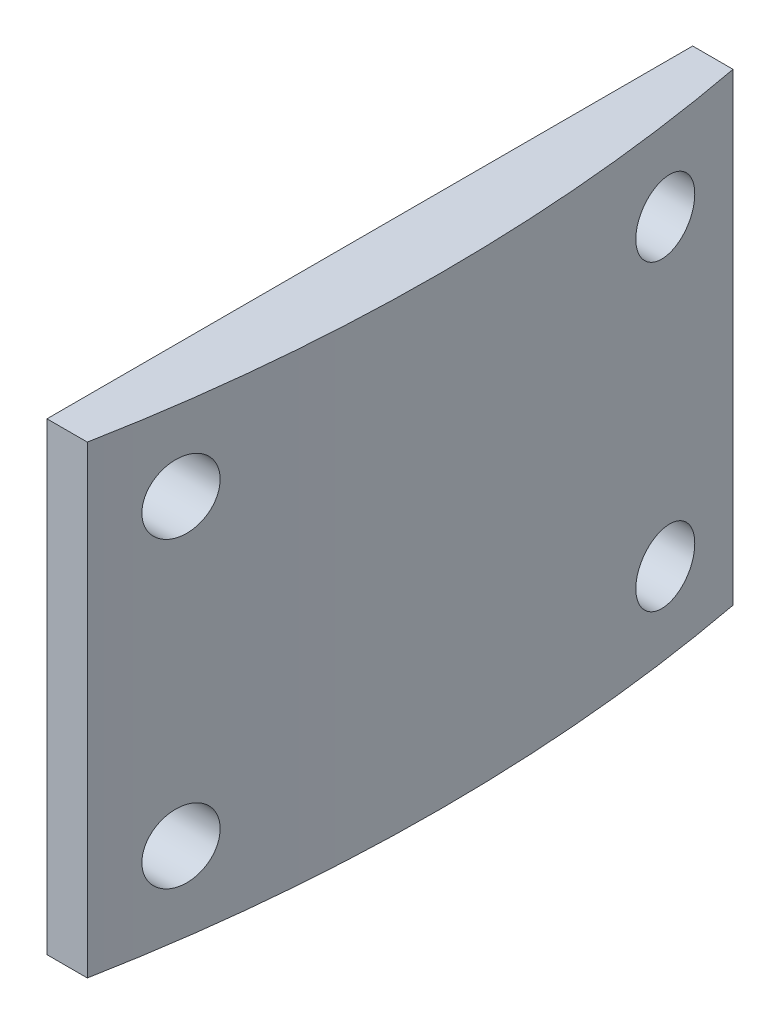
SolidWorks part; units mm, degrees
ref_plane "Спереди" through (0, 0, 0) normal (0, 0, 1) x (1, 0, 0)
ref_plane "Сверху" through (0, 0, 0) normal (0, 1, 0) x (1, 0, 0)
ref_plane "Справа" through (0, 0, 0) normal (1, 0, 0) x (0, 0, -1)
sketch "Эскиз1" plane through (0, 0, 0) normal (0, 1, 0) x (1, 0, 0)
  line L0 (-1.5015, 16) -> (-1.5015, -16) construction
  line L2 (-1.5015, 16) -> (-3.5015, 16)
  line L3 (-3.5015, 16) -> (-3.5015, -16)
  line L4 (-3.5015, -16) -> (-1.5015, -16)
  arc A0 (-1.5015, 16) -> (-1.5015, -16) centre (-86, 0) cw
  point P3 (0, 0)
  dimension "D3" = 86
  dimension "D1" = 2
  dimension "D2" = 32
extrude "Бобышка-Вытянуть1" add sketch "Эскиз1" along normal blind 23
sketch "Эскиз2" plane through (-3.5015, 0, 0) normal (-1, 0, 0) x (0, 0, 1)
  line L0 (0, 11.5) -> (0, 0) construction
  line L1 (-12, 19) -> (12, 19)
  line L2 (-12, 19) -> (-12, 4)
  line L3 (-12, 4) -> (12, 4)
  line L4 (12, 19) -> (12, 4)
  line L5 (-12, 19) -> (12, 4) construction
  line L6 (-12, 4) -> (12, 19) construction
  line L7 (-16, 0) -> (16, 0) construction
  circle A0 centre (-12, 19) radius 1.7
  circle A1 centre (-12, 4) radius 1.7
  circle A2 centre (12, 4) radius 1.7
  circle A3 centre (12, 19) radius 1.7
  point P0 (0, 11.5)
  dimension "D4" = 3.4
  dimension "D5" = 3.4
  dimension "D6" = 3.4
  dimension "D7" = 3.4
  dimension "D1" = 4
  dimension "D2" = 15
  dimension "D3" = 24
extrude "Вырез-Вытянуть1" cut sketch "Эскиз2" against normal through all contours L2 A1 L3 | L3 A1 L2 | L2 A0 L1 | L1 A0 L2 | L4 A3 L1 | L1 A3 L4 | L3 A2 L4 | L4 A2 L3
